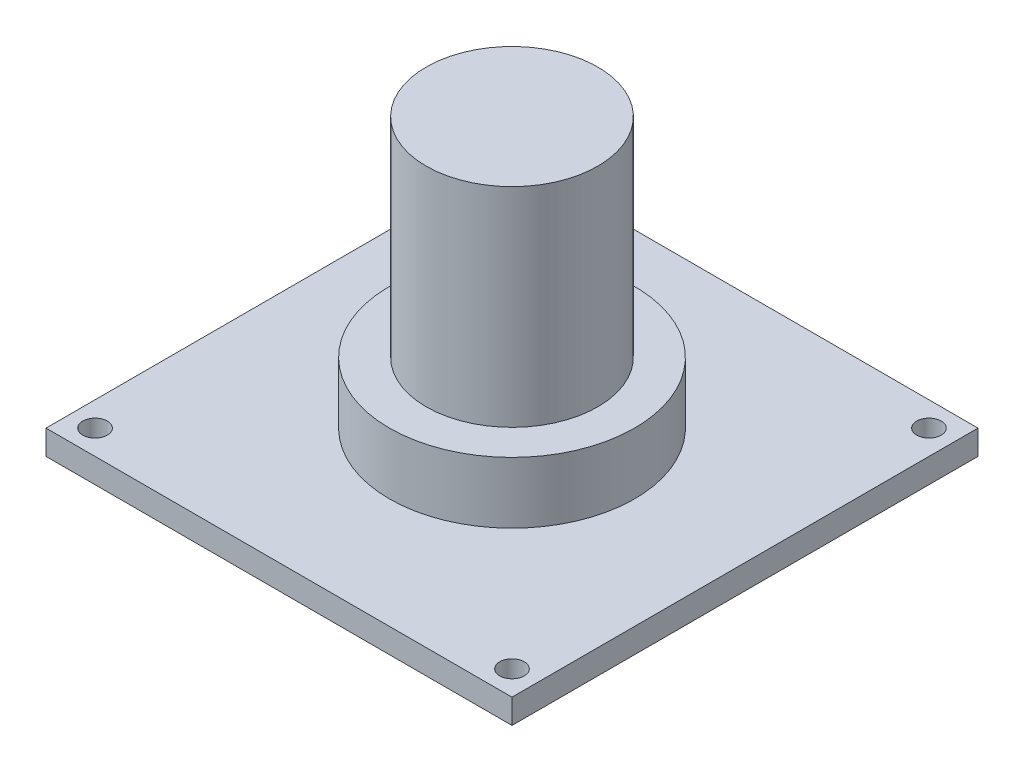
SolidWorks part; units mm, degrees
ref_plane "前视基准面" through (0, 0, 0) normal (0, 0, 1) x (1, 0, 0)
ref_plane "上视基准面" through (0, 0, 0) normal (0, 1, 0) x (1, 0, 0)
ref_plane "右视基准面" through (0, 0, 0) normal (1, 0, 0) x (0, 0, -1)
sketch "Sketch1" plane through (0, 0, 0) normal (0, 1, 0) x (1, 0, 0)
  line L1 (-19, -19) -> (19, -19)
  line L2 (-19, -19) -> (-19, 19)
  line L3 (-19, 19) -> (19, 19)
  line L4 (19, -19) -> (19, 19)
  line L5 (-19, -19) -> (19, 19) construction
  line L6 (-19, 19) -> (19, -19) construction
  line L7 (-17, -17) -> (17, -17) construction
  line L8 (-17, -17) -> (-17, 17) construction
  line L9 (-17, 17) -> (17, 17) construction
  line L10 (17, -17) -> (17, 17) construction
  line L11 (-17, -17) -> (17, 17) construction
  line L12 (-17, 17) -> (17, -17) construction
  circle A0 centre (-17, 17) radius 1
  circle A1 centre (17, 17) radius 1
  circle A2 centre (17, -17) radius 1
  circle A3 centre (-17, -17) radius 1
  point P0 (0, 0)
  point P6 (0, 0)
  dimension "D3" = 2
  dimension "D1" = 38
  dimension "D2" = 38
  dimension "D4" = 2
extrude "Boss-Extrude1" add sketch "Sketch1" along normal blind 2
sketch "Sketch2" plane through (0, 2, 0) normal (0, 1, 0) x (1, 0, 0)
  circle A0 centre (0, 0) radius 10
  dimension "D1" = 20
extrude "Boss-Extrude2" add sketch "Sketch2" along normal blind 5
sketch "Sketch3" plane through (0, 7, 0) normal (0, 1, 0) x (1, 0, 0)
  circle A0 centre (0, 0) radius 7
  dimension "D1" = 14
extrude "Boss-Extrude3" add sketch "Sketch3" along normal blind 17
